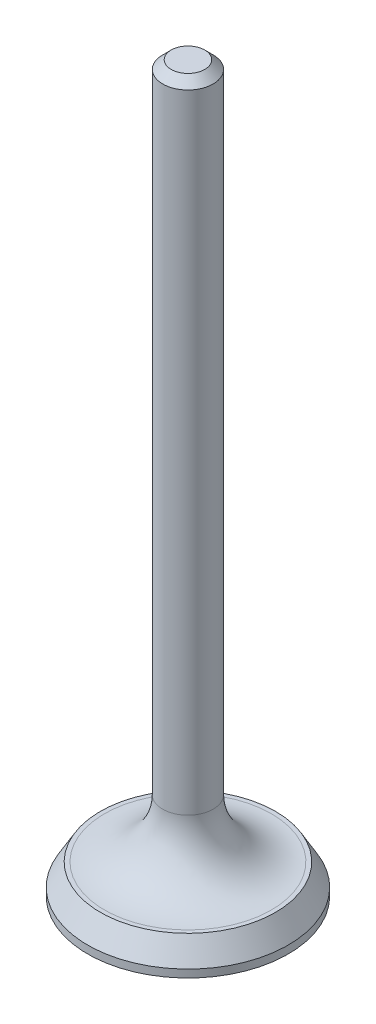
SolidWorks part; units mm, degrees
material "Литая легированная сталь"
ref_plane "Спереди" through (0, 0, 0) normal (0, 0, 1) x (1, 0, 0)
ref_plane "Сверху" through (0, 0, 0) normal (0, 1, 0) x (1, 0, 0)
ref_plane "Справа" through (0, 0, 0) normal (1, 0, 0) x (0, 0, -1)
sketch "Эскиз1" plane through (0, 0, 0) normal (0, 0, 1) x (1, 0, 0)
  line L0 (0, 0) -> (0, 112)
  line L1 (0, 112) -> (2.6, 112)
  line L2 (2.6, 112) -> (3.9, 110.7)
  line L3 (3.9, 110.7) -> (3.9, 13.6)
  line L4 (0, 0) -> (15.5, 0)
  line L6 (13.537, 4.6) -> (12.9, 4.6)
  line L7 (15.5, 0) -> (15.5, 1.2)
  line L8 (15.5, 1.2) -> (13.537, 4.6)
  arc A0 (12.9, 4.6) -> (3.9, 13.6) centre (12.9, 13.6) cw
  dimension "D6" = 9
  dimension "D1" = 112
  dimension "D2" = 45
  dimension "D3" = 2.6
  dimension "D4" = 1.3
  dimension "D5" = 15.5
  dimension "D7" = 1.2
  dimension "D8" = 4.6
  dimension "D9" = 210
revolve "Повернуть1" add sketch "Эскиз1" angle 360 about L0
